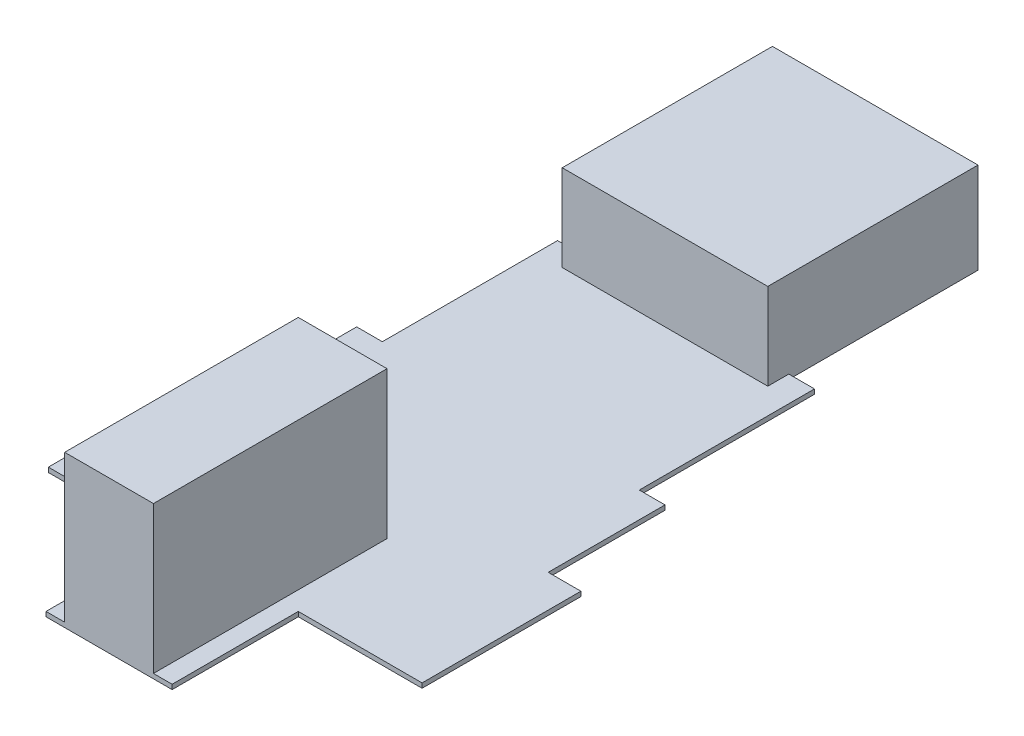
SolidWorks part; units mm, degrees
ref_plane "Спереди" through (0, 0, 0) normal (0, 0, 1) x (1, 0, 0)
ref_plane "Сверху" through (0, 0, 0) normal (0, 1, 0) x (1, 0, 0)
ref_plane "Справа" through (0, 0, 0) normal (1, 0, 0) x (0, 0, -1)
sketch "Sketch2" plane through (0, 0, 0) normal (0, 1, 0) x (1, 0, 0)
  line L0 (-1000, 0) -> (49000, 0) construction
  line L1 (0, -1000) -> (0, 49000) construction
  line L2 (-27, 0) -> (27, 0)
  line L3 (27, 0) -> (27, 54)
  line L4 (27, 54) -> (80, 54)
  line L5 (80, 54) -> (80, 122)
  line L6 (80, 122) -> (66, 122)
  line L7 (66, 122) -> (66, 172)
  line L8 (66, 172) -> (55, 172)
  line L9 (55, 172) -> (55, 247)
  line L10 (55, 247) -> (44, 247)
  line L11 (44, 247) -> (44, 328)
  line L12 (44, 328) -> (-44, 328)
  line L13 (1000, 0) -> (-49000, 0) construction
  line L14 (-44, 247) -> (-44, 328)
  line L15 (-55, 247) -> (-44, 247)
  line L16 (-66, 122) -> (-66, 172)
  line L17 (-80, 122) -> (-66, 122)
  line L18 (-80, 54) -> (-80, 122)
  line L19 (-27, 54) -> (-80, 54)
  line L20 (-27, 0) -> (-27, 54)
  line L21 (-55, 172) -> (-55, 247)
  line L22 (-66, 172) -> (-55, 172)
  point P28 (0, 0)
  point P29 (0, 328)
extrude "Boss-Extrude1" add sketch "Sketch2" along normal blind 2
sketch "Sketch3" plane through (0, 0, 0) normal (1, 0, 0) x (0, 0, -1)
  line L0 (0, 0) -> (0, 2) construction
  line L2 (0, 2) -> (100, 2)
  line L3 (0, 2) -> (0, 65)
  line L4 (0, 65) -> (100, 65)
  line L5 (100, 2) -> (100, 65)
extrude "Boss-Extrude2" add sketch "Sketch3" against normal blind 19 and the other way blind 19
sketch "Sketch6" plane through (0, 0, 0) normal (1, 0, 0) x (0, 0, -1)
  line L1 (328, 2) -> (238, 2)
  line L2 (328, 2) -> (328, 39)
  line L3 (328, 39) -> (238, 39)
  line L4 (238, 2) -> (238, 39)
  point P5 (496.5831, -16.2523)
extrude "Boss-Extrude3" add sketch "Sketch6" along normal up to vertex and the other way up to vertex
